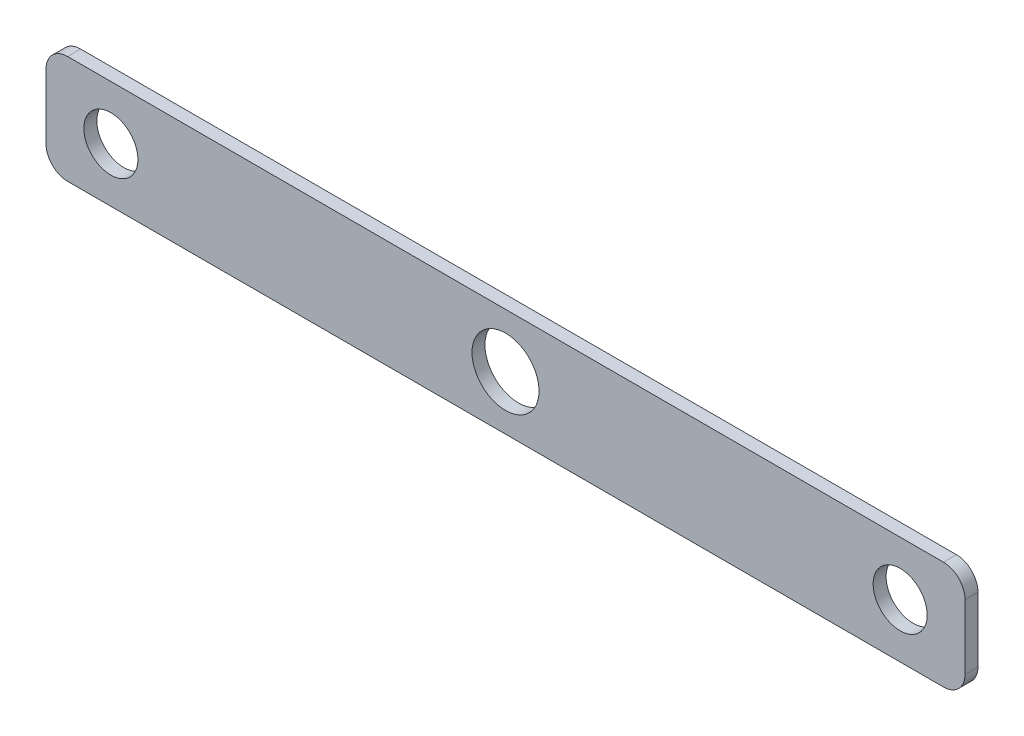
SolidWorks part; units mm, degrees
material "Plain Carbon Steel"
ref_plane "Front Plane" through (0, 0, 0) normal (0, 0, 1) x (1, 0, 0)
ref_plane "Top Plane" through (0, 0, 0) normal (0, 1, 0) x (1, 0, 0)
ref_plane "Right Plane" through (0, 0, 0) normal (1, 0, 0) x (0, 0, -1)
sketch "Sketch1" plane through (0, 0, 0) normal (0, 0, 1) x (1, 0, 0)
  line L0 (-132.6143, 0) -> (132.6143, 0) construction
  line L1 (0, 50.9398) -> (0, -50.9398) construction
  line L2 (107.95, 12.7) -> (-107.95, 12.7)
  line L3 (107.95, -12.7) -> (107.95, 12.7)
  line L4 (-107.95, -12.7) -> (107.95, -12.7)
  line L5 (-107.95, 12.7) -> (-107.95, -12.7)
  circle A0 centre (92.71, 0) radius 6.35
  circle A1 centre (0, 0) radius 7.874
  circle A2 centre (-92.71, 0) radius 6.35
  dimension "D3" = 12.7
  dimension "D5" = 15.748
  dimension "D1" = 215.9
  dimension "D2" = 25.4
  dimension "D4" = 185.42
extrude "Extrude1" add sketch "Sketch1" along normal mid plane 3.048
fillet "Fillet1" radius 5.08 4 edges at (107.95, 12.7, 0) (107.95, -12.7, 0) (-107.95, -12.7, 0) (-107.95, 12.7, 0)
